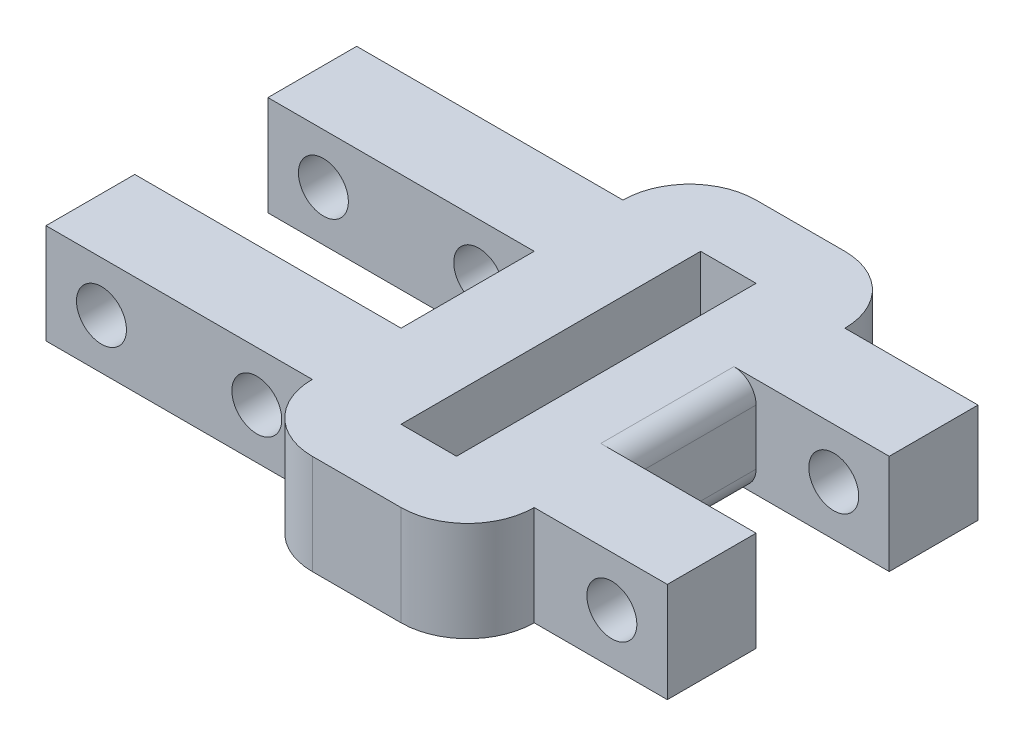
SolidWorks part; units mm, degrees
ref_plane "Front" through (0, 0, 0) normal (0, 0, 1) x (1, 0, 0)
ref_plane "Top" through (0, 0, 0) normal (0, 1, 0) x (1, 0, 0)
ref_plane "Right" through (0, 0, 0) normal (1, 0, 0) x (0, 0, -1)
sketch "Croquis1" plane through (0, 0, 0) normal (0, 1, 0) x (1, 0, 0)
  line L0 (-223.043, 0) -> (10929.1056, 0) construction
  line L1 (0, -223.043) -> (0, 10929.1056) construction
  line L2 (-223.043, -2.5) -> (10929.1056, -2.5) construction
  line L3 (-2, -10) -> (2, -10)
  line L4 (-5, -992.5198) -> (-5, 49007.4802) construction
  line L5 (-2, 10) -> (2, 10)
  line L6 (11, 7) -> (5, 7)
  line L7 (-5, -10) -> (5, 10) construction
  line L8 (-5, 10) -> (5, -10) construction
  line L9 (-223.043, 2.5) -> (10929.1056, 2.5) construction
  line L10 (-5, 7) -> (-17, 7)
  line L11 (-1.25, -6.75) -> (1.25, -6.75)
  line L12 (-1.25, -6.75) -> (-1.25, 6.75)
  line L13 (-1.25, 6.75) -> (1.25, 6.75)
  line L14 (1.25, -6.75) -> (1.25, 6.75)
  line L15 (-1.25, -6.75) -> (1.25, 6.75) construction
  line L16 (-1.25, 6.75) -> (1.25, -6.75) construction
  line L17 (-17, 7) -> (-17, 3)
  line L18 (-17, 3) -> (-5, 3)
  line L19 (-5, 3) -> (-5, -3)
  line L20 (-5, -3) -> (-17, -3)
  line L21 (-5, -7) -> (-17, -7)
  line L22 (-17, -3) -> (-17, -7)
  line L23 (11, -7) -> (11, -3)
  line L24 (11, -3) -> (5, -3)
  line L25 (11, -7) -> (5, -7)
  line L26 (11, 7) -> (11, 3)
  line L27 (11, 3) -> (5, 3)
  line L28 (5, 3) -> (5, -3)
  arc A0 (-5, 7) -> (-2, 10) centre (-2, 7) cw
  arc A1 (-2, -10) -> (-5, -7) centre (-2, -7) cw
  arc A2 (5, 7) -> (2, 10) centre (2, 7) ccw
  arc A3 (5, -7) -> (2, -10) centre (2, -7) cw
  point P4 (0, 0)
  point P22 (0, 0)
  point P32 (0.6, 0)
  dimension "D3" = 12
  dimension "D5" = 3
  dimension "D6" = 3
  dimension "D7" = 13.5
  dimension "D8" = 2.5
  dimension "D14" = 3
  dimension "D15" = 6
  dimension "D1" = 20
  dimension "D2" = 10
  dimension "D11" = 14
  dimension "D12" = 12
  dimension "D16" = 6
  dimension "D17" = 4
  dimension "D9" = 2.5
  dimension "D10" = 2.5
extrude "Saliente-Extruir1" add sketch "Croquis1" along normal blind 4.5
ref_plane "Plano1" through (0, 0, 3.5) normal (0, 0, 1) x (1, 0, 0)
sketch "Croquis7" plane through (0, 0, 3.5) normal (0, 0, 1) x (1, 0, 0)
  line L0 (-1000, 0) -> (49000, 0) construction
  line L1 (-1000.1155, 2.25) -> (48999.8845, 2.25) construction
  line L2 (0, -1000) -> (0, 49000) construction
  line L3 (11, 4.5) -> (11, 0) construction
  line L4 (-17, 4.5) -> (-17, 0) construction
  line L5 (-11, -995.5) -> (-11, 49004.5) construction
  line L6 (-17, 4.5) -> (-5, 4.5) construction
  circle A0 centre (-14.5, 2.25) radius 1.125
  circle A1 centre (8.5, 2.25) radius 1.125
  circle A2 centre (-7.5, 2.25) radius 1.125
  point P20 (-11, 4.5)
  dimension "D2" = 2.25
  dimension "D3" = 2.25
  dimension "D4" = 2.5
  dimension "D5" = 2.5
  dimension "D1" = 2.25
extrude "Cortar-Extruir4" cut sketch "Croquis7" against normal through all and the other way blind 10
sketch "Croquis2" plane through (0, 4.5, 0) normal (0, 1, 0) x (1, 0, 0)
  line L0 (0, -1000) -> (0, 49000) construction
  line L1 (-1000, 0) -> (49000, 0) construction
  line L2 (-1000, -6.5) -> (49000, -6.5) construction
  line L3 (-1000, 6.5) -> (49000, 6.5) construction
  line L4 (5, -1000) -> (5, 49000) construction
  line L5 (-7, -1000) -> (-7, 49000) construction
  line L6 (-5, 6.5) -> (-1.5, 6.5)
  line L7 (-1.5, 6.5) -> (-1.5, 4.5)
  line L8 (-1.5, 4.5) -> (-5, 4.5)
  line L9 (-5, 4.5) -> (-5, 6.5)
  line L10 (-5, -4.5) -> (-5, -6.5)
  line L11 (-1.5, -4.5) -> (-5, -4.5)
  line L12 (-1.5, -6.5) -> (-1.5, -4.5)
  line L13 (-5, -6.5) -> (-1.5, -6.5)
  line L14 (5, -4.5) -> (5, -6.5)
  line L15 (5, -6.5) -> (1.5, -6.5)
  line L16 (1.5, -6.5) -> (1.5, -4.5)
  line L17 (1.5, -4.5) -> (5, -4.5)
  point P16 (-3.25, 6.5)
  dimension "D5" = 3.5
  dimension "D6" = 2
  dimension "D7" = 1.5
  dimension "D1" = 6.5
  dimension "D2" = 6.5
  dimension "D3" = 5
extrude "Saliente-Extruir2" [suppressed] add sketch "Croquis2" along normal blind 9
sketch "Croquis3" [suppressed] plane through (0, 0, 6.5) normal (0, 0, 1) x (1, 0, 0)
  line L2 (0, -1000) -> (0, 49000) construction
  line L3 (1.5, 12) -> (5, 12) construction
  line L5 (1.5, 12) -> (1.5, 3) construction
  circle A1 centre (3.5, 10) radius 1.125
  dimension "D1" = 2
  dimension "D2" = 2
extrude "Cortar-Extruir1" [suppressed] cut sketch "Croquis3" against normal up to surface (13 mm away)
sketch "Croquis4" [suppressed] plane through (0, 0, 6.5) normal (0, 0, 1) x (1, 0, 0)
  line L0 (-3.25, -993) -> (-3.25, 49007) construction
  line L1 (-5, 12) -> (-1.5, 12) construction
  line L2 (-1007.7153, 10.45) -> (48992.2847, 10.45) construction
  line L4 (-1.5, 12) -> (-1.5, 3) construction
  line L5 (-5, 12) -> (-1.5, 12)
  line L6 (-5, 12) -> (-5, 10.45)
  line L7 (-5, 10.45) -> (-1.5, 10.45)
  line L8 (-1.5, 12) -> (-1.5, 10.45)
  point P5 (-3.25, 12)
  dimension "D1" = 1.55
extrude "Cortar-Extruir2" [suppressed] cut sketch "Croquis4" against normal up to surface (13 mm away)
fillet "Redondeo1" [suppressed] radius 2
sketch "Croquis5" [suppressed] plane through (-5, 0, 0) normal (-1, 0, 0) x (0, 0, 1)
  line L0 (6.5, 12) -> (6.5, 3) construction
  line L1 (4.5, 12) -> (6.5, 12)
  line L2 (4.5, 12) -> (4.5, 8)
  line L3 (4.5, 8) -> (6.5, 8)
  line L4 (6.5, 12) -> (6.5, 8)
  line L5 (0, -1000) -> (0, 49000) construction
  line L6 (-7, 0) -> (7, 0) construction
  line L7 (-4.5, 12) -> (-4.5, 8)
  line L8 (-4.5, 8) -> (-6.5, 8)
  line L9 (-6.5, 12) -> (-6.5, 8)
  line L10 (-4.5, 12) -> (-6.5, 12)
  point P12 (0, 0)
  dimension "D1" = 4
extrude "Saliente-Extruir3" [suppressed] add sketch "Croquis5" along normal blind 4
sketch "Croquis6" [suppressed] plane through (0, 0, 6.5) normal (0, 0, 1) x (1, 0, 0)
  line L0 (-5, 8) -> (-9, 12) construction
  line L1 (-9, 8) -> (-5.25, 12) construction
  line L2 (-9, 12) -> (-1.5, 12) construction
  circle A0 centre (-7, 10) radius 1.125
  dimension "D1" = 2.25
extrude "Cortar-Extruir3" [suppressed] cut sketch "Croquis6" against normal through all
fillet "Redondeo2" [suppressed] radius 1
fillet "Redondeo3" radius 1 2 edges at (5, 0, 0) (5, 4.5, 0)
